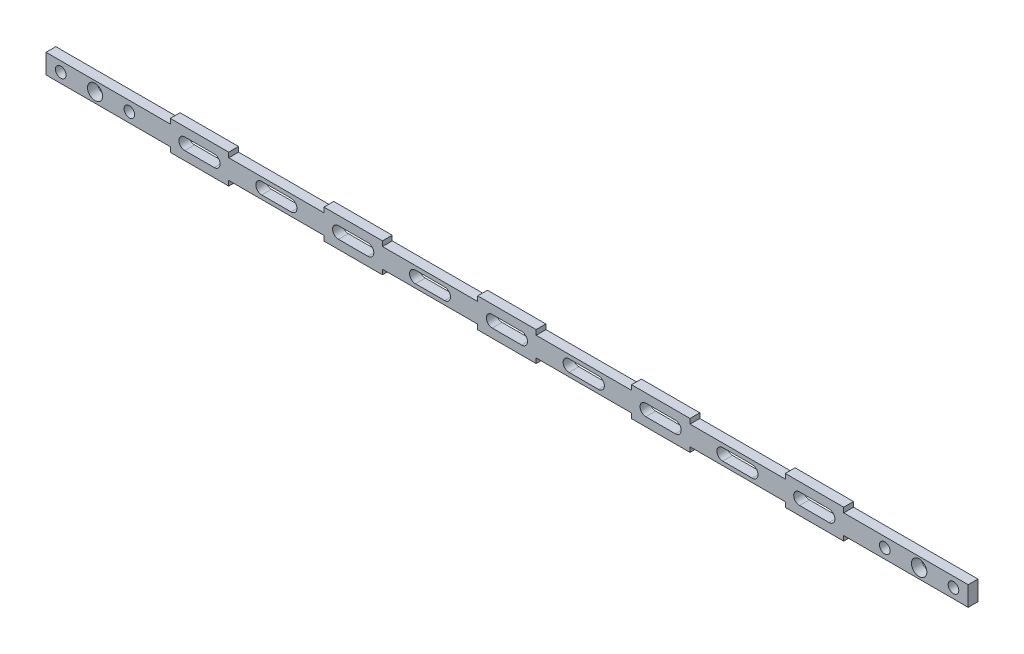
SolidWorks part; units mm, degrees
material "Acrylic (Medium-high impact)"
ref_plane "Plan de face" through (0, 0, 0) normal (0, 0, 1) x (1, 0, 0)
ref_plane "Plan de dessus" through (0, 0, 0) normal (0, 1, 0) x (1, 0, 0)
ref_plane "Plan de droite" through (0, 0, 0) normal (1, 0, 0) x (0, 0, -1)
sketch "Sketch1" plane through (0, 0, 0) normal (0, 0, 1) x (1, 0, 0)
  line L6 (298.45, -6.35) -> (-298.45, -6.35)
  line L9 (298.45, -6.35) -> (298.45, 6.35)
  line L10 (298.45, 6.35) -> (-298.45, 6.35)
  line L12 (-298.45, -6.35) -> (-298.45, 6.35)
  line L13 (298.45, -6.35) -> (-298.45, 6.35) construction
  line L14 (298.45, 6.35) -> (-298.45, -6.35) construction
  point P0 (0, 0)
  dimension "D1" = 596.9
  dimension "D2" = 12.7
extrude "Boss-Extrude1" add sketch "Sketch1" along normal blind 6.35
sketch "Sketch3" plane through (0, 6.35, 0) normal (0, 1, 0) x (1, 0, 0)
  line L5 (298.45, 0) -> (-298.45, 0) construction
  line L6 (-218.0167, 0) -> (-180.1707, 0)
  line L7 (-218.0167, 0) -> (-218.0167, -6.35)
  line L8 (-218.0167, -6.35) -> (-180.1707, -6.35)
  line L9 (-180.1707, 0) -> (-180.1707, -6.35)
  line L10 (298.45, -6.35) -> (-298.45, -6.35) construction
  line L12 (-118.5333, 0) -> (-80.6873, 0)
  line L13 (-118.5333, 0) -> (-118.5333, -6.35)
  line L14 (-118.5333, -6.35) -> (-80.6873, -6.35)
  line L15 (-80.6873, 0) -> (-80.6873, -6.35)
  line L16 (-19.05, 0) -> (18.796, 0)
  line L17 (-19.05, 0) -> (-19.05, -6.35)
  line L18 (-19.05, -6.35) -> (18.796, -6.35)
  line L19 (18.796, 0) -> (18.796, -6.35)
  line L20 (80.5603, 0) -> (118.4063, 0)
  line L21 (80.5603, 0) -> (80.5603, -6.35)
  line L22 (80.5603, -6.35) -> (118.4063, -6.35)
  line L23 (118.4063, 0) -> (118.4063, -6.35)
  line L24 (180.0437, 0) -> (217.8897, 0)
  line L25 (180.0437, 0) -> (180.0437, -6.35)
  line L26 (180.0437, -6.35) -> (217.8897, -6.35)
  line L27 (217.8897, 0) -> (217.8897, -6.35)
  point P8 (-99.6103, 0)
  point P9 (-199.0937, 0)
  point P26 (-0.127, 0)
  point P27 (99.4833, 0)
  point P31 (198.9667, 0)
  dimension "D1" = 37.846
  dimension "D2" = 99.4833
  dimension "D3" = 37.846
  dimension "D4" = 37.846
  dimension "D5" = 37.846
  dimension "D6" = 37.846
  dimension "D7" = 99.4833
  dimension "D8" = 99.4833
  dimension "D9" = 99.4833
extrude "Boss-Extrude2" add sketch "Sketch3" along normal blind 3.175
mirror "Mirror1" about plane through (0, 0, 0) normal (0, 1, 0) of "Boss-Extrude2"
sketch "Sketch4" plane through (0, 0, 0) normal (0, 0, -1) x (-1, 0, 0)
  line L0 (-298.45, -6.35) -> (-298.45, 6.35) construction
  circle A0 centre (-288.925, 0) radius 3.429
  circle A2 centre (-244.475, 0) radius 3.429
  circle A3 centre (-266.7, 0) radius 4.8895
  dimension "D4" = 6.858
  dimension "D5" = 6.858
  dimension "D6" = 9.779
  dimension "D1" = 9.525
  dimension "D2" = 31.75
  dimension "D3" = 44.45
extrude "Cut-Extrude1" cut sketch "Sketch4" against normal through all
mirror "Mirror2" about plane through (0, 0, 0) normal (1, 0, 0) of "Cut-Extrude1"
sketch "Sketch5" plane through (0, 0, 0) normal (0, 0, -1) x (-1, 0, 0)
  line L0 (-298.45, -6.35) -> (-298.45, 6.35) construction
  circle A0 centre (-266.7, 0) radius 4.9784
  dimension "D1" = 9.9568
  dimension "D2" = 31.75
extrude "Cut-Extrude2" cut sketch "Sketch5" against normal through all
sketch "Sketch6" plane through (0, 0, 6.35) normal (0, 0, 1) x (1, 0, 0)
  line L0 (-208.6187, 0) -> (-189.5687, 0) construction
  line L1 (-208.6187, 3.81) -> (-189.5687, 3.81)
  line L2 (-208.6187, -3.81) -> (-189.5687, -3.81)
  line L3 (-218.0167, 9.525) -> (-180.1707, 9.525) construction
  line L8 (-109.1353, 0) -> (-90.0853, 0) construction
  line L11 (-109.1353, 3.81) -> (-90.0853, 3.81)
  line L12 (-109.1353, -3.81) -> (-90.0853, -3.81)
  line L13 (-9.652, 0) -> (9.398, 0) construction
  line L14 (-9.652, 3.81) -> (9.398, 3.81)
  line L15 (-9.652, -3.81) -> (9.398, -3.81)
  line L16 (89.8313, 0) -> (108.8813, 0) construction
  line L17 (89.8313, 3.81) -> (108.8813, 3.81)
  line L18 (89.8313, -3.81) -> (108.8813, -3.81)
  line L19 (189.3147, 0) -> (208.3647, 0) construction
  line L20 (189.3147, 3.81) -> (208.3647, 3.81)
  line L21 (189.3147, -3.81) -> (208.3647, -3.81)
  line L22 (-158.877, 0) -> (-139.827, 0) construction
  line L23 (-158.877, 3.81) -> (-139.827, 3.81)
  line L24 (-158.877, -3.81) -> (-139.827, -3.81)
  line L25 (-59.3195, 0) -> (-40.4179, 0) construction
  line L26 (-59.3195, 3.81) -> (-40.4179, 3.81)
  line L27 (-59.3195, -3.81) -> (-40.4179, -3.81)
  line L28 (40.0897, 0) -> (59.1397, 0) construction
  line L29 (40.0897, 3.81) -> (59.1397, 3.81)
  line L30 (40.0897, -3.81) -> (59.1397, -3.81)
  line L31 (139.573, 0) -> (158.623, 0) construction
  line L32 (139.573, 3.81) -> (158.623, 3.81)
  line L33 (139.573, -3.81) -> (158.623, -3.81)
  line L34 (-180.1707, -6.35) -> (-118.5333, -6.35) construction
  line L35 (-199.0937, 0) -> (-149.352, 0) construction
  line L36 (-149.352, 0) -> (-99.6103, 0) construction
  line L37 (-99.6103, 0) -> (-49.8687, 0) construction
  line L38 (-49.8687, 0) -> (-0.127, 0) construction
  line L39 (-0.127, 0) -> (49.6147, 0) construction
  line L40 (49.6147, 0) -> (99.3563, 0) construction
  line L41 (99.3563, 0) -> (149.098, 0) construction
  line L42 (149.098, 0) -> (198.8397, 0) construction
  arc A0 (-208.6187, 3.81) -> (-208.6187, -3.81) centre (-208.6187, 0) ccw
  arc A1 (-189.5687, -3.81) -> (-189.5687, 3.81) centre (-189.5687, 0) ccw
  arc A8 (-109.1353, 3.81) -> (-109.1353, -3.81) centre (-109.1353, 0) ccw
  arc A9 (-90.0853, -3.81) -> (-90.0853, 3.81) centre (-90.0853, 0) ccw
  arc A10 (-9.652, 3.81) -> (-9.652, -3.81) centre (-9.652, 0) ccw
  arc A11 (9.398, -3.81) -> (9.398, 3.81) centre (9.398, 0) ccw
  arc A12 (89.8313, 3.81) -> (89.8313, -3.81) centre (89.8313, 0) ccw
  arc A13 (108.8813, -3.81) -> (108.8813, 3.81) centre (108.8813, 0) ccw
  arc A14 (189.3147, 3.81) -> (189.3147, -3.81) centre (189.3147, 0) ccw
  arc A15 (208.3647, -3.81) -> (208.3647, 3.81) centre (208.3647, 0) ccw
  arc A16 (-158.877, 3.81) -> (-158.877, -3.81) centre (-158.877, 0) ccw
  arc A17 (-139.827, -3.81) -> (-139.827, 3.81) centre (-139.827, 0) ccw
  arc A18 (-59.3195, 3.81) -> (-59.3195, -3.81) centre (-59.3195, 0) ccw
  arc A19 (-40.4179, -3.81) -> (-40.4179, 3.81) centre (-40.4179, 0) ccw
  arc A20 (40.0897, 3.81) -> (40.0897, -3.81) centre (40.0897, 0) ccw
  arc A21 (59.1397, -3.81) -> (59.1397, 3.81) centre (59.1397, 0) ccw
  arc A22 (139.573, 3.81) -> (139.573, -3.81) centre (139.573, 0) ccw
  arc A23 (158.623, -3.81) -> (158.623, 3.81) centre (158.623, 0) ccw
  point P2 (-199.0937, 0)
  point P7 (0, 0)
  point P12 (-199.0937, 9.525)
  point P14 (-99.6103, 0)
  point P21 (-0.127, 0)
  point P28 (99.3563, 0)
  point P35 (198.8397, 0)
  point P44 (-149.352, 0)
  point P51 (-49.8687, 0)
  point P58 (49.6147, 0)
  point P65 (149.098, 0)
  point P72 (-149.352, -6.35)
  point P82 (-53.2571, 20.5814)
  dimension "D1" = 7.62
  dimension "D2" = 19.05
  dimension "D3" = 49.7417
  dimension "D4" = 19.05
  dimension "D5" = 19.05
  dimension "D6" = 9.4508
  dimension "D7" = 19.05
  dimension "D8" = 19.05
  dimension "D9" = 19.05
  dimension "D10" = 19.05
  dimension "D11" = 19.05
  dimension "D12" = 7.62
  dimension "D13" = 7.62
  dimension "D14" = 7.62
  dimension "D15" = 7.62
  dimension "D16" = 7.62
  dimension "D17" = 7.62
  dimension "D18" = 7.62
  dimension "D19" = 7.62
extrude "Cut-Extrude3" cut sketch "Sketch6" against normal through all
